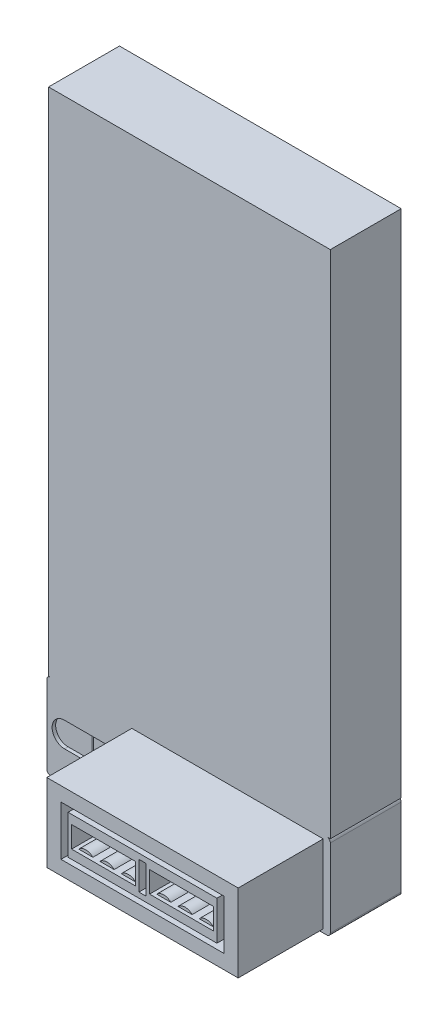
SolidWorks part; units mm, degrees
ref_plane "前视基准面" through (0, 0, 0) normal (0, 0, 1) x (1, 0, 0)
ref_plane "上视基准面" through (0, 0, 0) normal (0, 1, 0) x (1, 0, 0)
ref_plane "右视基准面" through (0, 0, 0) normal (1, 0, 0) x (0, 0, -1)
sketch "草图1" plane through (0, 0, 0) normal (0, 0, 1) x (1, 0, 0)
  line L1 (13.5, -5.5) -> (-13.5, -5.5)
  line L2 (13.5, -5.5) -> (13.5, 5.5)
  line L3 (13.5, 5.5) -> (-13.5, 5.5)
  line L4 (-13.5, -5.5) -> (-13.5, 5.5)
  line L5 (13.5, -5.5) -> (-13.5, 5.5) construction
  line L6 (13.5, 5.5) -> (-13.5, -5.5) construction
  point P0 (0, 0)
  dimension "D1" = 11
  dimension "D2" = 27
extrude "凸台-拉伸1" add sketch "草图1" along normal blind 12
sketch "草图2" plane through (0, 0, 12) normal (0, 0, 1) x (1, 0, 0)
  line L1 (11.5, -3.5) -> (-11.5, -3.5)
  line L2 (11.5, -3.5) -> (11.5, 3.5)
  line L3 (11.5, 3.5) -> (-11.5, 3.5)
  line L4 (-11.5, -3.5) -> (-11.5, 3.5)
  line L5 (11.5, -3.5) -> (-11.5, 3.5) construction
  line L6 (11.5, 3.5) -> (-11.5, -3.5) construction
  point P0 (0, 0)
  dimension "D1" = 7
  dimension "D2" = 23
extrude "切除-拉伸1" cut sketch "草图2" against normal blind 8
sketch "草图3" plane through (0, 0, 4) normal (0, 0, 1) x (1, 0, 0)
  line L0 (0, 5.5) -> (0, -5.5) construction
  line L1 (13.5, 5.5) -> (-13.5, 5.5) construction
  line L2 (-13.5, -5.5) -> (13.5, -5.5) construction
  line L3 (-13.5, 0) -> (13.5, 0) construction
  line L4 (-13.5, 5.5) -> (-13.5, -5.5) construction
  line L5 (13.5, -5.5) -> (13.5, 5.5) construction
  line L7 (10.5, -2.75) -> (-10.5, -2.75)
  line L8 (10.5, -2.75) -> (10.5, 2.75)
  line L9 (10.5, 2.75) -> (-10.5, 2.75)
  line L10 (-10.5, -2.75) -> (-10.5, 2.75)
  line L11 (10.5, -2.75) -> (-10.5, 2.75) construction
  line L12 (10.5, 2.75) -> (-10.5, -2.75) construction
  point P12 (0, 0)
  dimension "D1" = 5.5
  dimension "D2" = 21
extrude "凸台-拉伸2" add sketch "草图3" along normal blind 8
sketch "草图4" plane through (0, 0, 12) normal (0, 0, 1) x (1, 0, 0)
  line L0 (0, 2.75) -> (0, -2.75) construction
  line L1 (10.5, 2.75) -> (-10.5, 2.75) construction
  line L2 (-10.5, -2.75) -> (10.5, -2.75) construction
  line L3 (-5.5, 2.75) -> (-5.5, -2.75) construction
  line L4 (10.5, 2.75) -> (-10.5, 2.75) construction
  line L5 (-10.5, -2.75) -> (10.5, -2.75) construction
  line L6 (-10.5, 0) -> (10.5, 0) construction
  line L7 (-10.5, 2.75) -> (-10.5, -2.75) construction
  line L8 (10.5, -2.75) -> (10.5, 2.75) construction
  line L9 (1, -1.5) -> (1, 1.5)
  line L10 (-1, -1.5) -> (-10, -1.5)
  line L11 (-1, -1.5) -> (-1, 1.5)
  line L12 (-1, 1.5) -> (-10, 1.5)
  line L13 (-10, -1.5) -> (-10, 1.5)
  line L14 (-1, -1.5) -> (-10, 1.5) construction
  line L15 (-1, 1.5) -> (-10, -1.5) construction
  line L22 (1, -1.5) -> (10, -1.5)
  line L23 (10, -1.5) -> (10, 1.5)
  line L24 (1, 1.5) -> (10, 1.5)
  point P18 (-5.5, 0)
  point P23 (0, 0)
  dimension "D1" = 9
  dimension "D2" = 5.5
  dimension "D3" = 3
extrude "切除-拉伸2" cut sketch "草图4" against normal blind 4
sketch "草图5" plane through (0, 0, 12) normal (0, 0, 1) x (1, 0, 0)
  line L0 (0, 2.75) -> (0, -2.75) construction
  line L1 (10.5, 2.75) -> (-10.5, 2.75) construction
  line L2 (-10.5, -2.75) -> (10.5, -2.75) construction
  line L4 (0.5, -2) -> (-0.5, -2)
  line L5 (0.5, -2) -> (0.5, 2)
  line L6 (0.5, 2) -> (-0.5, 2)
  line L7 (-0.5, -2) -> (-0.5, 2)
  line L8 (0.5, -2) -> (-0.5, 2) construction
  line L9 (0.5, 2) -> (-0.5, -2) construction
  point P6 (0, 0)
  dimension "D1" = 1
  dimension "D2" = 4
extrude "切除-拉伸3" cut sketch "草图5" against normal blind 1
sketch "草图6" plane through (0, 0, 8) normal (0, 0, 1) x (1, 0, 0)
  line L0 (-5.5, -1.5) -> (-5.5, 1.5) construction
  line L1 (-10, -1.5) -> (-1, -1.5) construction
  line L2 (-1, 1.5) -> (-10, 1.5) construction
  line L3 (-8.5, 1.5) -> (-8.5, -1.5) construction
  line L4 (-1, 1.5) -> (-10, 1.5) construction
  line L5 (-9.5, 1.5) -> (-9.5, -1.5) construction
  line L6 (-7.5, 1.5) -> (-7.5, -1.5) construction
  line L7 (-6.5, 1.5) -> (-6.5, -1.5) construction
  line L8 (-7.5, -1.5) -> (-9.5, -1.5)
  line L9 (-4.5, 1.5) -> (-4.5, -1.5) construction
  line L10 (-4.5, -1.5) -> (-6.5, -1.5)
  line L11 (-3.5, -1.5) -> (-1.5, -1.5)
  line L12 (0, 2.75) -> (0, -2.75) construction
  line L13 (10.5, 2.75) -> (-10.5, 2.75) construction
  line L14 (-10.5, -2.75) -> (10.5, -2.75) construction
  line L15 (3.5, -1.5) -> (1.5, -1.5)
  line L16 (4.5, -1.5) -> (6.5, -1.5)
  line L17 (7.5, -1.5) -> (9.5, -1.5)
  arc A0 (-9.5, -1.5) -> (-7.5, -1.5) centre (-8.5, -2.5) cw
  arc A1 (-6.5, -1.5) -> (-4.5, -1.5) centre (-5.5, -2.5) cw
  arc A2 (-1.5, -1.5) -> (-3.5, -1.5) centre (-2.5, -2.5) ccw
  arc A3 (1.5, -1.5) -> (3.5, -1.5) centre (2.5, -2.5) cw
  arc A4 (6.5, -1.5) -> (4.5, -1.5) centre (5.5, -2.5) ccw
  arc A5 (9.5, -1.5) -> (7.5, -1.5) centre (8.5, -2.5) ccw
  dimension "D4" = 1.4142
  dimension "D6" = 1.4142
  dimension "D1" = 3
  dimension "D2" = 1
  dimension "D3" = 1
  dimension "D5" = 1
extrude "凸台-拉伸3" add sketch "草图6" along normal blind 3.5
sketch "草图7" plane through (0, 0, 0) normal (0, 0, -1) x (-1, 0, 0)
  line L0 (-13.5, -5.5) -> (-13.5, 5.5) construction
  line L1 (-14, -6) -> (25, -6)
  line L2 (-14.5, -5.5) -> (-14.5, 5.5)
  line L3 (-14, 6) -> (25, 6)
  line L4 (25.5, -5.5) -> (25.5, 5.5)
  line L5 (-13.5, 5.5) -> (13.5, 5.5) construction
  arc A0 (-14.5, 5.5) -> (-14, 6) centre (-14, 5.5) cw
  arc A1 (-14, -6) -> (-14.5, -5.5) centre (-14, -5.5) cw
  arc A2 (25.5, 5.5) -> (25, 6) centre (25, 5.5) ccw
  arc A3 (25, -6) -> (25.5, -5.5) centre (25, -5.5) ccw
  point P10 (-14.5, -6)
  point P15 (25.5, -6)
  dimension "D4" = 0.5
  dimension "D5" = 0.5
  dimension "D6" = 0.5
  dimension "D7" = 0.5
  dimension "D1" = 1
  dimension "D2" = 40
  dimension "D3" = 12
  dimension "D8" = 0.5
extrude "凸台-拉伸4" add sketch "草图7" along normal blind 10
sketch "草图8" plane through (0, 0, 0) normal (0, 0, 1) x (1, 0, 0)
  line L0 (-25.5, 0) -> (-13.5, 0) construction
  line L1 (-25.5, -5.5) -> (-25.5, 5.5) construction
  line L2 (-13.5, 5.5) -> (-13.5, -5.5) construction
  line L3 (-19.5, 6) -> (-19.5, -6) construction
  line L4 (-25, 6) -> (14, 6) construction
  line L5 (14, -6) -> (-25, -6) construction
  line L6 (-25.5, 1.75) -> (-13.5, 1.75) construction
  line L7 (-25.5, -1.75) -> (-13.5, -1.75) construction
  line L8 (-23, 6) -> (-23, -6) construction
  line L9 (-16, 6) -> (-16, -6) construction
  line L10 (-23, 1.75) -> (-16, 1.75)
  line L11 (-16, -1.75) -> (-23, -1.75)
  arc A0 (-23, 1.75) -> (-23, -1.75) centre (-23, 0) ccw
  arc A1 (-16, 1.75) -> (-16, -1.75) centre (-16, 0) cw
  dimension "D1" = 6
  dimension "D2" = 1.75
  dimension "D3" = 3.5
extrude "切除-拉伸4" cut sketch "草图8" against normal blind 0.5
sketch "草图9" plane through (0, 0, -0.5) normal (0, 0, 1) x (1, 0, 0)
  line L0 (-19.5, 1.75) -> (-19.5, -1.75) construction
  line L1 (-16, 1.75) -> (-23, 1.75) construction
  line L2 (-23, -1.75) -> (-16, -1.75) construction
  line L3 (-24.75, 0) -> (-14.25, 0) construction
  line L5 (-19.4, -1.75) -> (-19.6, -1.75)
  line L6 (-19.4, -1.75) -> (-19.4, 1.75)
  line L7 (-19.4, 1.75) -> (-19.6, 1.75)
  line L8 (-19.6, -1.75) -> (-19.6, 1.75)
  line L9 (-19.4, -1.75) -> (-19.6, 1.75) construction
  line L10 (-19.4, 1.75) -> (-19.6, -1.75) construction
  arc A0 (-23, 1.75) -> (-23, -1.75) centre (-23, 0) ccw construction
  arc A1 (-16, -1.75) -> (-16, 1.75) centre (-16, 0) ccw construction
  point P14 (-19.5, 0)
  dimension "D1" = 0.2
extrude "凸台-拉伸5" add sketch "草图9" along normal blind 0.1
sketch "草图10" plane through (0, 6, 0) normal (0, -1, 0) x (1, 0, 0)
  line L0 (-25, 0) -> (-25.5, 0) construction
  line L1 (-25.25, 0) -> (14.5, 0)
  line L2 (-25.25, 0) -> (-25.25, -10)
  line L3 (-25.25, -10) -> (14.5, -10)
  line L4 (14.5, 0) -> (14.5, -10)
extrude "凸台-拉伸6" add sketch "草图10" against normal blind 72
